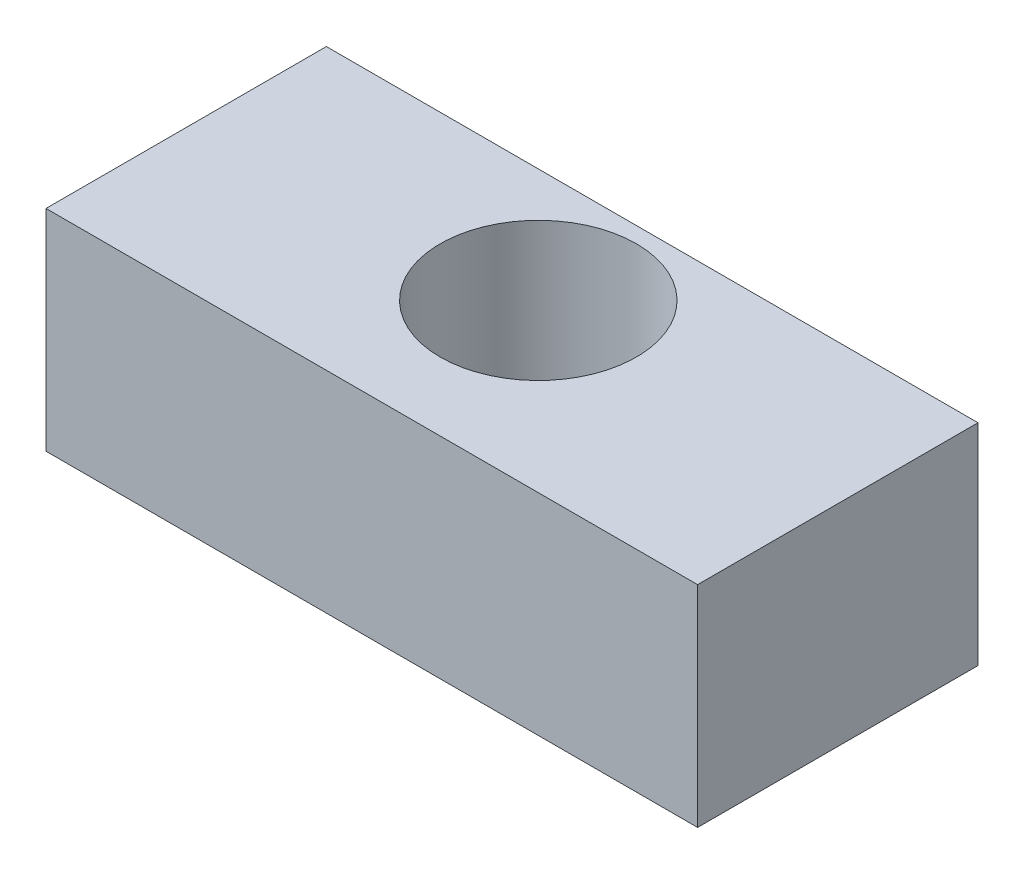
SolidWorks part; units mm, degrees
material "Polyethylene Cross-Linked"
ref_plane "Front Plane" through (0, 0, 0) normal (0, 0, 1) x (1, 0, 0)
ref_plane "Top Plane" through (0, 0, 0) normal (0, 1, 0) x (1, 0, 0)
ref_plane "Right Plane" through (0, 0, 0) normal (1, 0, 0) x (0, 0, -1)
sketch "Sketch1" plane through (0, 0, 0) normal (0, 1, 0) x (1, 0, 0)
  line L1 (0, 0) -> (29.5139, 0)
  line L2 (0, 0) -> (0, 12.7)
  line L3 (0, 12.7) -> (29.5139, 12.7)
  line L4 (29.5139, 0) -> (29.5139, 12.7)
  circle A0 centre (14.7569, 7.5406) radius 4.445
extrude "Boss-Extrude1" add sketch "Sketch1" along normal blind 9.525
sketch "Sketch3" plane through (0, 9.525, 0) normal (0, 1, 0) x (1, 0, 0)
